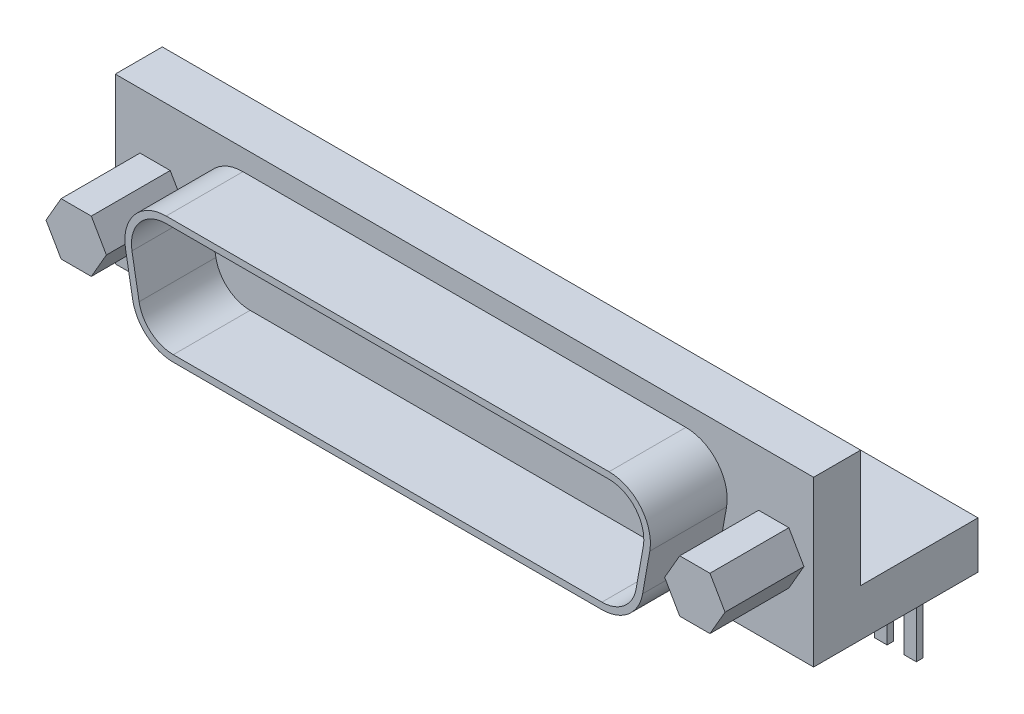
SolidWorks part; units mm, degrees
material "6061-T6 (SS)"
ref_plane "Front Plane" through (0, 0, 0) normal (0, 0, 1) x (1, 0, 0)
ref_plane "Top Plane" through (0, 0, 0) normal (0, 1, 0) x (1, 0, 0)
ref_plane "Right Plane" through (0, 0, 0) normal (1, 0, 0) x (0, 0, -1)
sketch "Sketch1" plane through (0, 0, 0) normal (1, 0, 0) x (0, 0, -1)
  line L1 (0, 0) -> (12.5, 0)
  line L2 (0, 0) -> (0, 12.5)
  line L3 (0, 12.5) -> (3.5774, 12.5)
  line L4 (12.5, 0) -> (12.5, 3.5774)
  line L7 (12.5, 3.5774) -> (3.5774, 3.5774)
  line L8 (3.5774, 12.5) -> (3.5774, 3.5774)
  dimension "D1" = 12.5
  dimension "D2" = 12.5
extrude "Boss-Extrude1" add sketch "Sketch1" along normal blind 53.1
sketch "Sketch2" plane through (0, 0, 0) normal (0, 0, 1) x (1, 0, 0)
  line L0 (9.4328, 10.2) -> (43.6672, 10.2)
  line L1 (45.7184, 7.7555) -> (45.0599, 4.0211)
  line L2 (43.0087, 2.3) -> (10.0913, 2.3)
  line L3 (8.0401, 4.0211) -> (7.3816, 7.7555)
  line L4 (26.55, 10.2) -> (26.55, 12.5) construction
  line L5 (53.1, 12.5) -> (0, 12.5) construction
  line L6 (14.9307, 2.3) -> (14.9307, 0) construction
  line L7 (53.1, 0) -> (0, 0) construction
  line L8 (0, 12.5) -> (0, 0) construction
  arc A0 (43.6672, 10.2) -> (45.7184, 7.7555) centre (43.6672, 8.1172) cw
  arc A1 (45.0599, 4.0211) -> (43.0087, 2.3) centre (43.0087, 4.3828) cw
  arc A2 (10.0913, 2.3) -> (8.0401, 4.0211) centre (10.0913, 4.3828) cw
  arc A3 (9.4328, 10.2) -> (7.3816, 7.7555) centre (9.4328, 8.1172) ccw
  dimension "D1" = 2.0828
  dimension "D3" = 38.4
  dimension "D2" = 7.9
  dimension "D4" = 10
extrude "Boss-Extrude2" [suppressed] add sketch "Sketch2" along normal blind 6
sketch "Sketch3" plane through (0, 0, 0) normal (0, -1, 0) x (1, 0, 0)
  line L0 (2.3955, -9.25) -> (3.6645, -9.75) construction
  line L1 (1.44, -9.25) -> (2.3955, -9.25)
  line L2 (1.44, -9.25) -> (1.44, -9.75)
  line L3 (1.44, -9.75) -> (2.3955, -9.75)
  line L4 (2.3955, -9.25) -> (2.3955, -9.75)
  line L5 (3.6645, -9.25) -> (4.62, -9.25)
  line L6 (3.6645, -9.25) -> (3.6645, -9.75)
  line L7 (3.6645, -9.75) -> (4.62, -9.75)
  line L8 (4.62, -9.25) -> (4.62, -9.75)
  line L9 (48.48, -9.25) -> (49.4355, -9.25)
  line L10 (48.48, -9.25) -> (48.48, -9.75)
  line L11 (48.48, -9.75) -> (49.4355, -9.75)
  line L12 (49.4355, -9.25) -> (49.4355, -9.75)
  line L13 (50.7045, -9.25) -> (51.66, -9.25)
  line L14 (50.7045, -9.25) -> (50.7045, -9.75)
  line L15 (50.7045, -9.75) -> (51.66, -9.75)
  line L16 (51.66, -9.25) -> (51.66, -9.75)
  line L17 (49.4355, -9.75) -> (50.7045, -9.25) construction
  line L18 (50.07, -9.5) -> (3.03, -9.5) construction
  line L19 (26.55, -9.5) -> (26.55, -12.5) construction
  line L20 (53.1, -12.5) -> (0, -12.5) construction
  line L21 (53.1, 0) -> (0, 0) construction
  dimension "D1" = 0.5
  dimension "D2" = 3.18
  dimension "D3" = 3.18
  dimension "D4" = 47.04
  dimension "D5" = 9.5
extrude "Boss-Extrude3" add sketch "Sketch3" along normal blind 5
sketch "Sketch4" plane through (0, 0, 0) normal (0, 0, 1) x (1, 0, 0)
  line L0 (3.03, 12.5) -> (3.03, 6.25) construction
  line L1 (4.178, 4.2616) -> (5.326, 6.25)
  line L2 (5.326, 6.25) -> (4.178, 8.2384)
  line L3 (4.178, 8.2384) -> (1.882, 8.2384)
  line L4 (1.882, 8.2384) -> (0.734, 6.25)
  line L5 (0.734, 6.25) -> (1.882, 4.2616)
  line L6 (1.882, 4.2616) -> (4.178, 4.2616)
  line L7 (51.218, 4.2616) -> (52.366, 6.25)
  line L8 (52.366, 6.25) -> (51.218, 8.2384)
  line L9 (51.218, 8.2384) -> (48.922, 8.2384)
  line L10 (48.922, 8.2384) -> (47.774, 6.25)
  line L11 (47.774, 6.25) -> (48.922, 4.2616)
  line L12 (48.922, 4.2616) -> (51.218, 4.2616)
  line L13 (53.1, 12.5) -> (0, 12.5) construction
  line L14 (3.03, 6.25) -> (3.03, 0) construction
  line L15 (53.1, 0) -> (0, 0) construction
  line L16 (3.03, 6.25) -> (26.55, 12.5) construction
  line L17 (26.55, 12.5) -> (50.07, 6.25) construction
  circle A0 centre (3.03, 6.25) radius 1.9884 construction
  circle A1 centre (50.07, 6.25) radius 1.9884 construction
  dimension "D1" = 47.04
extrude "Boss-Extrude4" add sketch "Sketch4" along normal blind 6
sketch "Sketch5" plane through (0, 0, 0) normal (0, -1, 0) x (1, 0, 0)
  line L1 (4.62, -9.25) -> (48.48, -9.25) construction
  line L2 (4.62, -9.25) -> (4.62, -9.75) construction
  line L3 (4.62, -9.75) -> (48.48, -9.75) construction
  line L4 (48.48, -9.25) -> (48.48, -9.75) construction
  line L5 (4.62, -9.25) -> (48.48, -9.75) construction
  line L6 (4.62, -9.75) -> (48.48, -9.25) construction
  point P0 (26.55, -9.5)
ref_point "EAGLEREF"
sketch "Sketch6" plane through (0, 0, 0) normal (0, 0, 1) x (1, 0, 0)
  line L0 (9.7116, 10.43) -> (43.3884, 10.43)
  line L1 (45.9899, 7.3297) -> (45.4473, 4.2529)
  line L2 (42.8459, 2.07) -> (10.2541, 2.07)
  line L3 (7.6527, 4.2529) -> (7.1101, 7.3297)
  line L4 (0, 12.5) -> (0, 0) construction
  line L5 (26.55, 12.5) -> (26.55, 10.93) construction
  line L7 (9.7116, 10.93) -> (43.3884, 10.93)
  line L8 (46.4823, 7.2429) -> (45.9397, 4.1661)
  line L9 (42.8459, 1.57) -> (10.2541, 1.57)
  line L10 (7.1603, 4.1661) -> (6.6177, 7.2429)
  line L11 (26.55, 1.57) -> (26.55, 0) construction
  line L12 (53.1, 12.5) -> (0, 12.5) construction
  arc A0 (43.3884, 10.43) -> (45.9899, 7.3297) centre (43.3884, 7.7884) cw
  arc A1 (45.4473, 4.2529) -> (42.8459, 2.07) centre (42.8459, 4.7116) cw
  arc A2 (10.2541, 2.07) -> (7.6527, 4.2529) centre (10.2541, 4.7116) cw
  arc A3 (9.7116, 10.43) -> (7.1101, 7.3297) centre (9.7116, 7.7884) ccw
  arc A4 (43.3884, 10.93) -> (46.4823, 7.2429) centre (43.3884, 7.7884) cw
  arc A5 (45.9397, 4.1661) -> (42.8459, 1.57) centre (42.8459, 4.7116) cw
  arc A6 (10.2541, 1.57) -> (7.1603, 4.1661) centre (10.2541, 4.7116) cw
  arc A7 (9.7116, 10.93) -> (6.6177, 7.2429) centre (9.7116, 7.7884) ccw
  point P34 (26.55, 10.4214)
  dimension "D1" = 2.6416
  dimension "D4" = 38.96
  dimension "D2" = 10
  dimension "D5" = 8.36
  dimension "D3" = 0.5
extrude "Boss-Extrude5" add sketch "Sketch6" along normal blind 5.84
